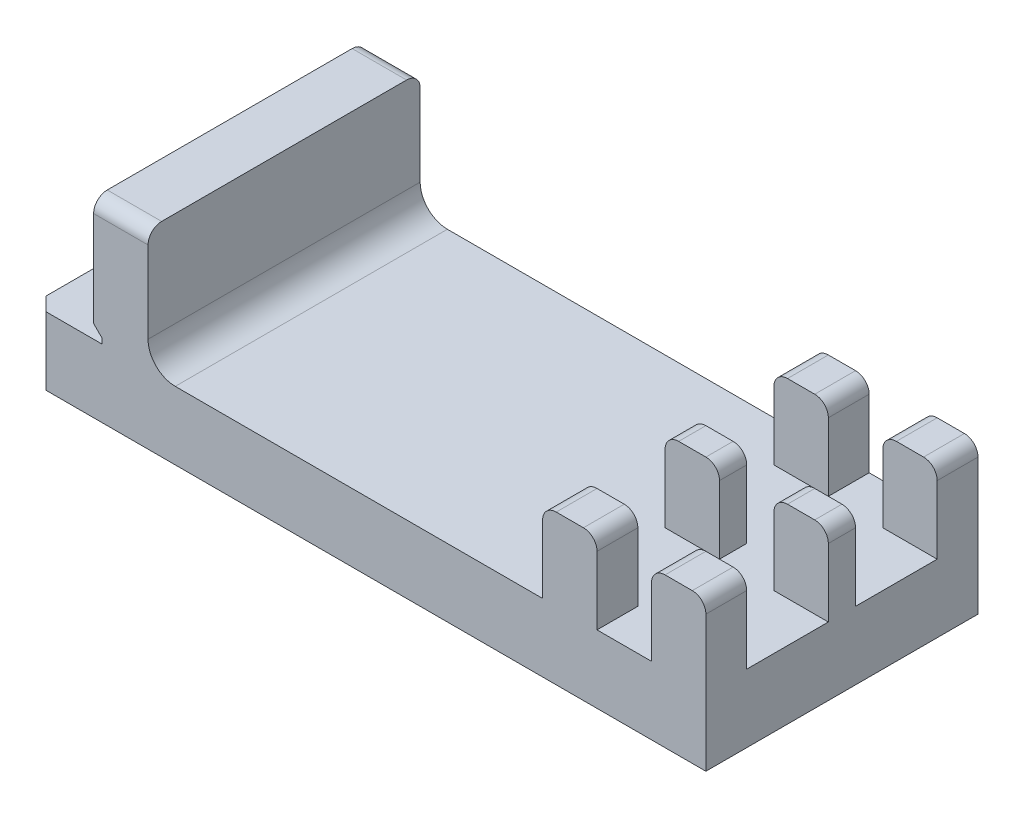
SolidWorks part; units mm, degrees
ref_plane "Přední rovina" through (0, 0, 0) normal (0, 0, 1) x (1, 0, 0)
ref_plane "Horní rovina" through (0, 0, 0) normal (0, 1, 0) x (1, 0, 0)
ref_plane "Pravá rovina" through (0, 0, 0) normal (1, 0, 0) x (0, 0, -1)
sketch "Skica1" plane through (0, 0, 0) normal (0, 0, 1) x (1, 0, 0)
  line L0 (-49.5, 0) -> (0, 0)
  line L1 (0, 0) -> (0, 11)
  line L2 (-41, 14) -> (-45, 14)
  line L3 (-45, 14) -> (-45, 5)
  line L4 (-45, 5) -> (-49.5, 5)
  line L5 (-49.5, 5) -> (-49.5, 0)
  line L6 (-41, 14) -> (-41, 5)
  line L7 (-41, 5) -> (-12, 5)
  line L8 (-12, 5) -> (-12, 11)
  line L9 (-12, 11) -> (-8, 11)
  line L10 (-8, 11) -> (-8, 5)
  line L11 (-8, 5) -> (-4, 5)
  line L12 (-4, 5) -> (-4, 11)
  line L13 (-4, 11) -> (0, 11)
  dimension "D1" = 4.5
  dimension "D2" = 5
  dimension "D3" = 14
  dimension "D4" = 45
  dimension "D5" = 4
  dimension "D6" = 4
  dimension "D7" = 4
  dimension "D8" = 5
  dimension "D9" = 6
  dimension "D10" = 4
extrude "Přidat vysunutím1" add sketch "Skica1" along normal mid plane 20
sketch "Skica2" plane through (0, 11, 0) normal (0, 1, 0) x (1, 0, 0)
  line L6 (-12, -10) -> (-12, 10) construction
  line L7 (-12, 7) -> (0, 7)
  line L8 (-12, 7) -> (-12, 1)
  line L9 (-12, 1) -> (0, 1)
  line L10 (0, 7) -> (0, 1)
  line L11 (0, -10) -> (0, 10) construction
  line L12 (-8, 10) -> (-12, 10) construction
  line L13 (-12, -1) -> (0, -1)
  line L14 (-12, -1) -> (-12, -7)
  line L15 (-12, -7) -> (0, -7)
  line L16 (0, -1) -> (0, -7)
  line L17 (-8, -10) -> (-12, -10) construction
  dimension "D1" = 2
  dimension "D2" = 3
  dimension "D3" = 3
extrude "Odebrat vysunutím1" cut sketch "Skica2" against normal up to surface (6 mm away) contours L9 L10 L7 L8 | L15 L16 L13 L14 up to face at (-26.5, 5, 0)
fillet "Zaoblit1" radius 1 14 edges at (0, 11, -8.5) (-4, 11, -8.5) (-8, 11, -8.5) (-12, 11, -8.5) (0, 11, 0) (-4, 11, 0) (-8, 11, 0) (-12, 11, 0) (0, 11, 8.5) (-4, 11, 8.5) (-12, 11, 8.5) (-8, 11, 8.5) (-43, 14, -10) (-43, 14, 10)
chamfer "Zkosení1" distance 1 angle 45 2 edges at (-49.5, 2.5, 10) (-49.5, 2.5, -10)
fillet "Zaoblit2" radius 2 1 edges at (-41, 5, 0)
sketch "Skica3" plane through (0, 0, 10) normal (0, 0, 1) x (1, 0, 0)
  line L0 (-45, 6) -> (-44.4, 5.4)
  line L1 (-45, 5) -> (-44.4, 5)
  line L2 (-45, 5) -> (-45, 6)
  line L5 (-44.4, 5) -> (-44.4, 5.4)
  line L6 (-45, 5) -> (-48.5, 5) construction
  dimension "D1" = 0.6
  dimension "D2" = 45
  dimension "D3" = 0.4
  dimension "D4" = 1
extrude "Odebrat vysunutím2" cut sketch "Skica3" against normal through all
